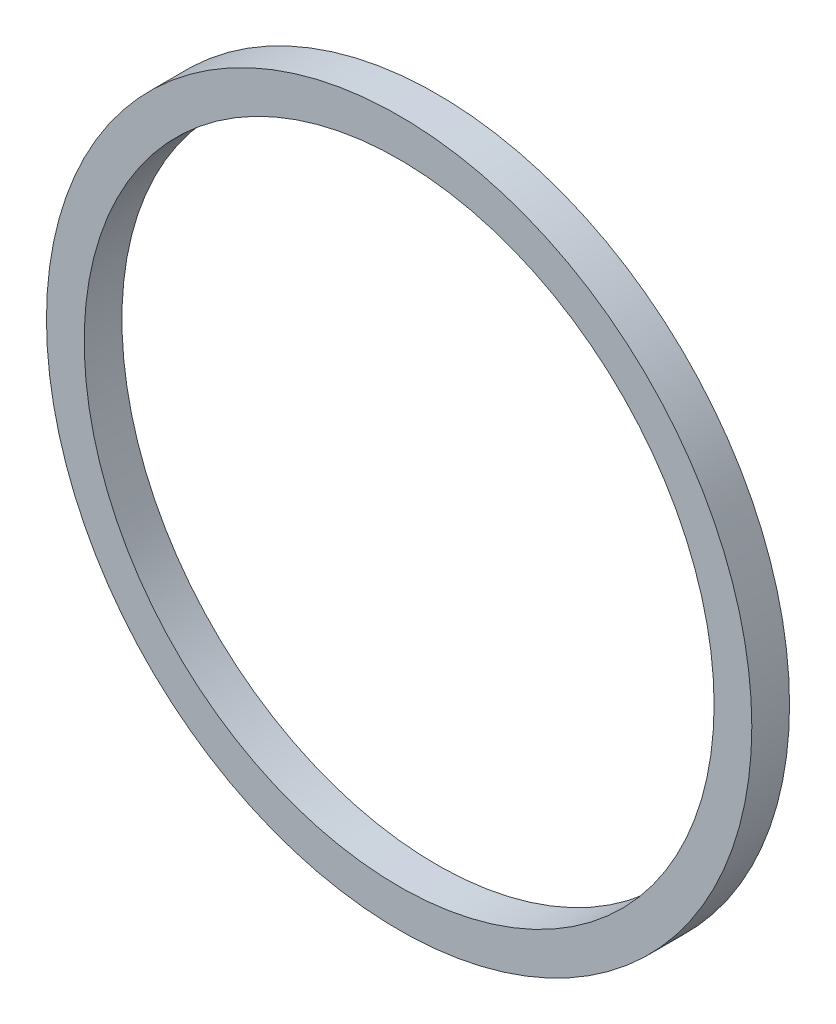
SolidWorks part; units mm, degrees
ref_plane "Front Plane" through (0, 0, 0) normal (0, 0, 1) x (1, 0, 0)
ref_plane "Top Plane" through (0, 0, 0) normal (0, 1, 0) x (1, 0, 0)
ref_plane "Right Plane" through (0, 0, 0) normal (1, 0, 0) x (0, 0, -1)
sketch "Sketch1" plane through (0, 0, 0) normal (0, 0, 1) x (1, 0, 0)
  line L0 (0, 21.209) -> (0, -21.209) construction
  circle A0 centre (0, 0) radius 21.209
  circle A1 centre (0, 0) radius 23.749
  dimension "D1" = 42.418
  dimension "D2" = 2.54
extrude "Boss-Extrude1" add sketch "Sketch1" along normal blind 2.54
sketch3d "3DSketch1"
  line L0 (0, 0, 0) -> (0, -23.749, 0) construction
  line L1 (0, -23.749, 0) -> (0, -23.749, -35.1464) construction
  circle A2 centre (0, -23.749, -35.1464) radius 23.749
  circle A5 centre (0, -23.749, -35.1464) radius 21.209
  circle A6 centre (0, 0, 0) radius 23.749 construction
  point P2 (0, -2.54, -35.1464)
  point P5 (0, 0, 23.749)
  point P8 (0, -23.749, 0)
  point P9 (0, -23.749, 0)
  point P10 (0, -23.749, 0)
  point P11 (0, -23.749, 0)
  point P13 (0, -23.749, 0)
  point P14 (0, 0, -35.1464)
  point P15 (0, 0, 0)
  point P16 (0, 0, 0)
  point P17 (0, -23.749, 0)
  point P18 (0, -23.749, 0)
  point P19 (0, -23.749, 0)
  point P20 (0, -23.749, 0)
  point P22 (0, -23.749, 0)
  dimension "D1" = 42.418
  dimension "D2" = 42.418
  dimension "D3" = 47.498
equation "\"FoamCore\" = \".2\""
equation "\"MDF\" = \".2\""
equation "\"GMaterial\"= \".2\""
equation "\"PVCMountDiameter\" = \"0.5in\""
equation "\"PVCMountDistanceToEdge\" = \"0.5\""
equation "\"PVCThickness\" = \"0.2in\""
equation "\"BaseWidth\" = \"10in\""
equation "\"BaseLength\" = \"8in\""
equation "\"BallDiameter\" = \"1.57in\""
equation "\"BaseGap\" = \"4in\""
equation "\"FunnelTopDiameter\" = \"8in\""
equation "\"FunnelTopDepth\" = \"1.5in\""
equation "\"BallGap\" = \"0.1in\""
equation "\"FunnelLength\" = 6in"
equation "\"FunnelMaterial\" = 0.1in"
equation "\"FunnelLowerDiameter\" = \"BallDiameter\"+\"BallGap\""
equation "\"FunnelDepth\" = 1.5in"
equation "\"AmmoFeederLength\" = 8in "
equation "\"AmmoFeederCutoffLength\" = 3in"
equation "\"D1@Sketch1\"=\"FunnelLowerDiameter\""
equation "\"D2@Sketch1\"=\"FunnelMaterial\""
equation "\"D1@3DSketch1\"=\"FunnelLowerDiameter\""
equation "\"D2@3DSketch1\"=\"FunnelLowerDiameter\""
equation "\"D3@3DSketch1\"=\"FunnelLowerDiameter\"+\"FunnelMaterial\"*2"
